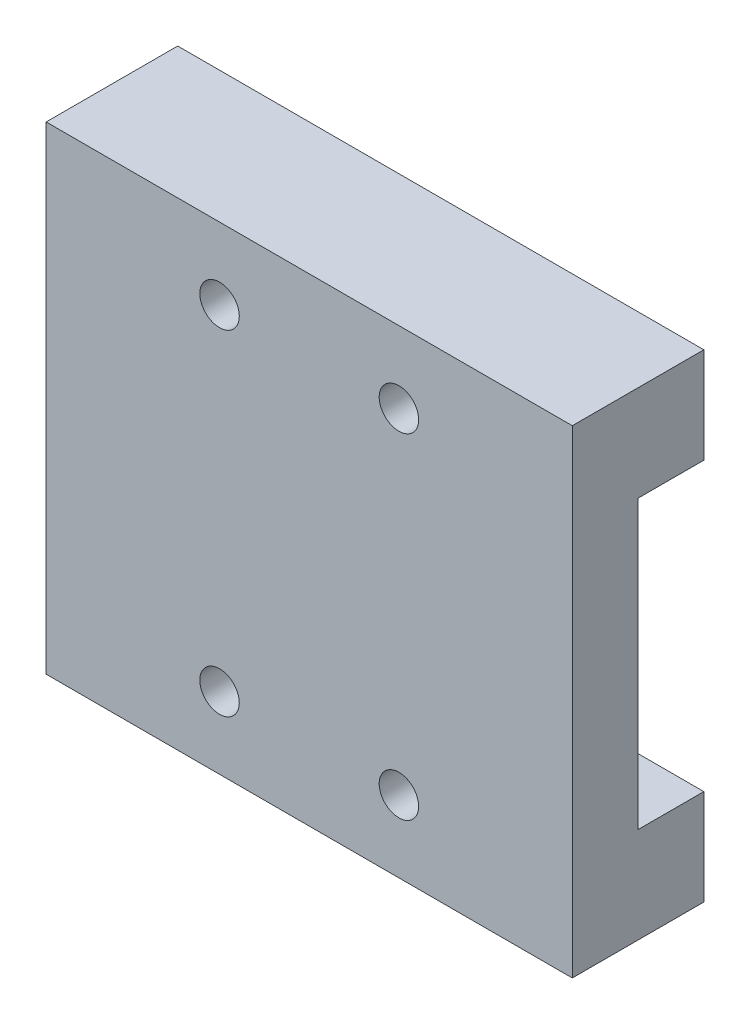
SolidWorks part; units mm, degrees
material "SKD11淬火HRC56-60"
ref_plane "前基準面" through (0, 0, 0) normal (0, 0, 1) x (1, 0, 0)
ref_plane "上基準面" through (0, 0, 0) normal (0, 1, 0) x (1, 0, 0)
ref_plane "右基準面" through (0, 0, 0) normal (1, 0, 0) x (0, 0, -1)
sketch "草图1" plane through (0, 0, 0) normal (0, 0, 1) x (1, 0, 0)
  line L1 (0, 0) -> (44, 0)
  line L2 (0, 0) -> (0, 40)
  line L3 (0, 40) -> (44, 40)
  line L4 (44, 0) -> (44, 40)
  dimension "D1" = 40
  dimension "D2" = 44
extrude "凸台-拉伸1" add sketch "草图1" along normal blind 11
sketch "草图2" plane through (0, 0, 0) normal (-1, 0, 0) x (0, 0, 1)
  line L0 (0, 40) -> (0, 0) construction
  line L1 (0, 8) -> (5.5, 8)
  line L2 (0, 8) -> (0, 32)
  line L3 (0, 32) -> (5.5, 32)
  line L4 (5.5, 8) -> (5.5, 32)
  line L5 (0, 20) -> (11, 20) construction
  line L6 (11, 40) -> (11, 0) construction
  dimension "D1" = 24
  dimension "D2" = 5.5
extrude "切除-拉伸1" cut sketch "草图2" against normal through all
hole_wizard "M4 螺纹孔1" positions "草图4" profile "草图3" tap size "M4" standard "ISO"
sketch "草图4" plane through (0, 0, 11) normal (0, 0, 1) x (1, 0, 0)
  line L0 (0, 20) -> (44, 20) construction
  line L1 (0, 40) -> (0, 0) construction
  line L2 (44, 0) -> (44, 40) construction
  line L3 (22, 40) -> (22, 0) construction
  line L4 (44, 40) -> (0, 40) construction
  line L5 (0, 0) -> (44, 0) construction
  point P0 (14.5, 34)
  point P1 (29.5, 34)
  point P3 (14.5, 6)
  point P5 (29.5, 6)
  dimension "D1" = 28
  dimension "D2" = 15
sketch "草图3" plane through (14.5, 34, 11) normal (1, 0, 0) x (0, -1, 0)
  line L0 (0, 0) -> (0, 11.0914)
  line L1 (0, 11.0914) -> (1.65, 10.1)
  line L2 (1.65, 10.1) -> (1.65, 0)
  line L5 (1.65, 0) -> (0, 0)
  line L10 (0, 11.0914) -> (-1.65, 10.1) construction
  line L11 (0, -6.35) -> (0, 107.95) construction
  dimension "螺纹孔钻头直径" = 3.3
  dimension "螺纹孔钻头深度" = 10.1
  dimension "导头角度" = 118
cosmetic thread "孔螺蚊线1" parameters "D1"=8, "D2"=4
cosmetic thread "孔螺蚊线2" parameters "D1"=8, "D2"=4
cosmetic thread "孔螺蚊线3" parameters "D1"=8, "D2"=4
cosmetic thread "孔螺蚊线4" parameters "D1"=8, "D2"=4
